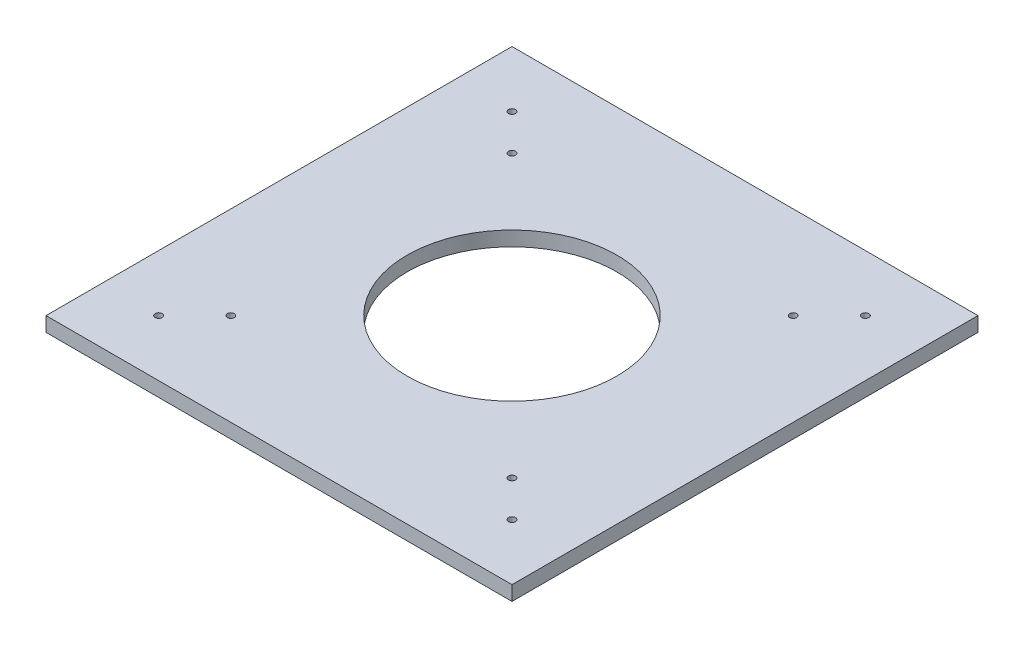
SolidWorks part; units mm, degrees
ref_plane "Front Plane" through (0, 0, 0) normal (0, 0, 1) x (1, 0, 0)
ref_plane "Top Plane" through (0, 0, 0) normal (0, 1, 0) x (1, 0, 0)
ref_plane "Right Plane" through (0, 0, 0) normal (1, 0, 0) x (0, 0, -1)
sketch "Sketch1" plane through (0, 0, 0) normal (0, 1, 0) x (1, 0, 0)
  line L0 (0, 80) -> (0, -80) construction
  line L1 (-80, -80) -> (80, -80)
  line L2 (-80, -80) -> (-80, 80)
  line L3 (-80, 80) -> (80, 80)
  line L4 (80, -80) -> (80, 80)
  line L5 (-80, -80) -> (80, 80) construction
  line L6 (-80, 80) -> (80, -80) construction
  line L7 (-80, 0) -> (80, 0) construction
  circle A0 centre (-60.6642, 60.6642) radius 1.2
  circle A1 centre (-48.2796, 48.2796) radius 1.2
  circle A2 centre (48.2796, 48.2796) radius 1.2
  circle A3 centre (60.6642, 60.6642) radius 1.2
  circle A4 centre (60.6642, -60.6642) radius 1.2
  circle A5 centre (48.2796, -48.2796) radius 1.2
  circle A6 centre (-48.2796, -48.2796) radius 1.2
  circle A7 centre (-60.6642, -60.6642) radius 1.2
  circle A8 centre (0, 0) radius 36
  point P0 (0, 0)
  dimension "D2" = 2.4
  dimension "D3" = 2.4
  dimension "D4" = 72
  dimension "D1" = 160
extrude "Boss-Extrude1" add sketch "Sketch1" along normal blind 5
